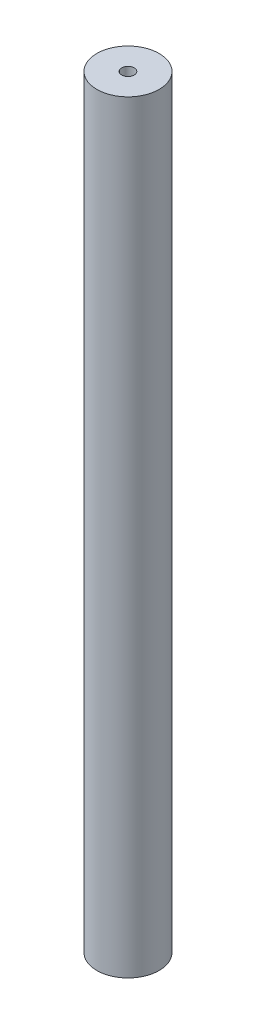
SolidWorks part; units mm, degrees
material "6061-T6 (SS)"
ref_plane "Front Plane" through (0, 0, 0) normal (0, 0, 1) x (1, 0, 0)
ref_plane "Top Plane" through (0, 0, 0) normal (0, 1, 0) x (1, 0, 0)
ref_plane "Right Plane" through (0, 0, 0) normal (1, 0, 0) x (0, 0, -1)
sketch "Sketch1" plane through (0, 0, 0) normal (0, 1, 0) x (1, 0, 0)
  circle A0 centre (0, 0) radius 12.7
  dimension "D1" = 25.4
extrude "Boss-Extrude1" add sketch "Sketch1" along normal mid plane 311.15
hole_wizard "1/4-20 Tapped Hole1" positions "3DSketch1" profile "Sketch2" tap size "1/4-20" standard "ANSI Inch"
sketch3d "3DSketch1"
  line L0 (0, 155.575, 0) -> (0, -155.575, 0) construction
  point P0 (0, 155.575, 0)
  point P4 (0, -155.575, 0)
sketch "Sketch2" plane through (0, 155.575, 0) normal (1, 0, 0) x (0, 0, 1)
  line L0 (0, 0) -> (0, 18.0438)
  line L1 (0, 18.0438) -> (2.5527, 16.51)
  line L2 (2.5527, 16.51) -> (2.5527, 0)
  line L5 (2.5527, 0) -> (0, 0)
  line L10 (0, 18.0438) -> (-2.5527, 16.51) construction
  line L11 (0, -6.35) -> (0, 107.95) construction
  dimension "Tap Drill Dia." = 5.1054
  dimension "Tap Drill Depth" = 16.51
  dimension "Drill Angle" = 118
cosmetic thread "Hole Thread1" parameters "D1"=12.7, "D2"=6.35
cosmetic thread "Hole Thread2" parameters "D1"=12.7, "D2"=6.35
